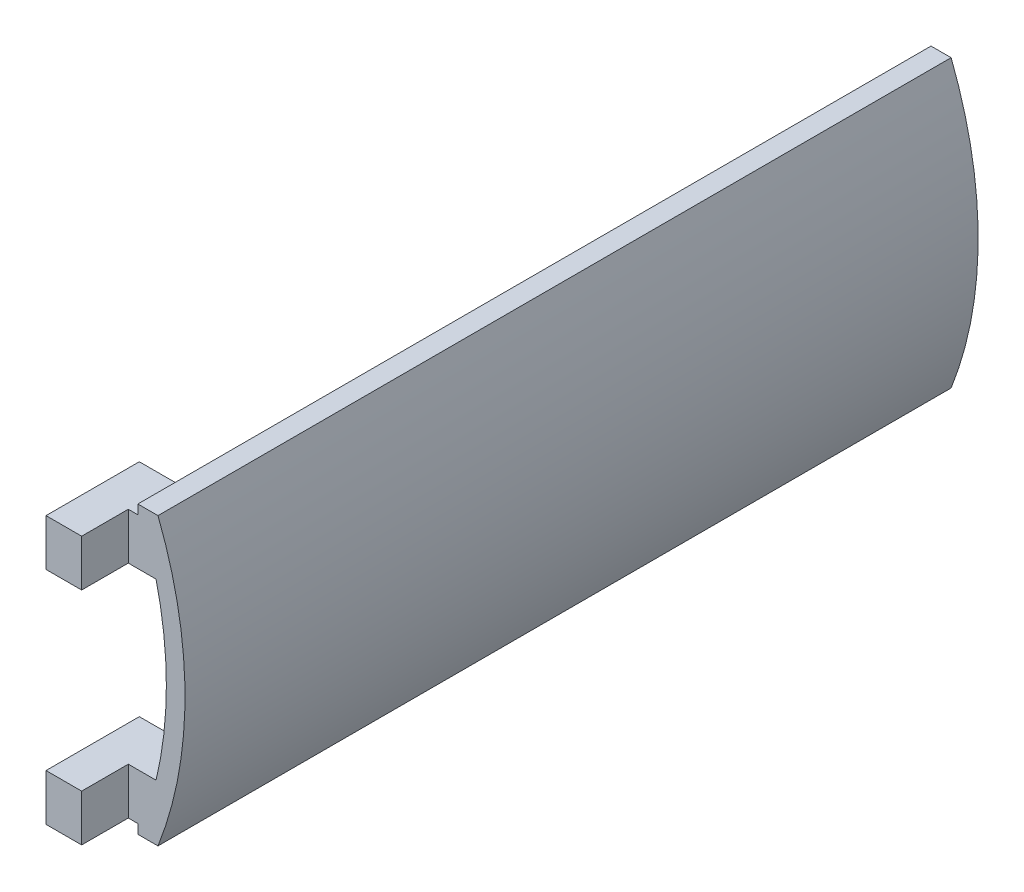
SolidWorks part; units mm, degrees
ref_plane "Спереди" through (0, 0, 0) normal (0, 0, 1) x (1, 0, 0)
ref_plane "Сверху" through (0, 0, 0) normal (0, 1, 0) x (1, 0, 0)
ref_plane "Справа" through (0, 0, 0) normal (1, 0, 0) x (0, 0, -1)
ref_plane "Плоскость4" through (0, 0, 0) normal (0, 0, -1) x (-1, 0, 0)
sketch "Эскиз1" plane through (0, 0, 0) normal (0, 0, -1) x (-1, 0, 0)
  line L0 (-36.9459, 15.3297) -> (-39.1024, 15.3297)
  line L1 (-39.1024, -15.3297) -> (-36.9459, -15.3297)
  arc A0 (-36.9459, -15.3297) -> (-36.9459, 15.3297) centre (0, 0) cw
  arc A1 (-39.1024, 15.3297) -> (-39.1024, -15.3297) centre (0, 0) ccw
extrude "Бобышка-Вытянуть1" add sketch "Эскиз1" against normal blind 85
ref_plane "Плоскость5" through (0, 0, 85) normal (0, 0, 1) x (1, 0, 0)
sketch "Эскиз2" plane through (0, 0, 85) normal (0, 0, 1) x (1, 0, 0)
  line L0 (36.9459, 15.3297) -> (36.9459, 14.3297)
  line L1 (36.9459, 14.3297) -> (32.1024, 14.3297)
  line L2 (32.1024, 14.3297) -> (32.1024, 9.3297)
  line L3 (32.1024, 9.3297) -> (38.8967, 9.3297)
  arc A0 (38.8967, 9.3297) -> (36.9459, 15.3297) centre (0, 0) ccw
extrude "Бобышка-Вытянуть2" add sketch "Эскиз2" against normal blind 5
sketch "Эскиз3" plane through (0, 0, 85) normal (0, 0, 1) x (1, 0, 0)
  line L0 (35.9229, 9.3297) -> (32.1024, 9.3297)
  line L1 (32.1024, 9.3297) -> (32.1024, 14.3297)
  line L2 (32.1024, 14.3297) -> (35.9229, 14.3297)
  line L3 (35.9229, 14.3297) -> (35.9229, 9.3297)
extrude "Бобышка-Вытянуть3" add sketch "Эскиз3" along normal blind 5
sketch "Эскиз4" plane through (0, 0, 85) normal (0, 0, 1) x (1, 0, 0)
  line L0 (32.1024, -14.3297) -> (36.9459, -14.3297)
  line L1 (36.9459, -14.3297) -> (36.9459, -15.3297)
  line L2 (38.8967, -9.3297) -> (32.1024, -9.3297)
  line L3 (32.1024, -9.3297) -> (32.1024, -14.3297)
  arc A0 (36.9459, -15.3297) -> (38.8967, -9.3297) centre (0, 0) ccw
extrude "Бобышка-Вытянуть4" add sketch "Эскиз4" against normal blind 5
sketch "Эскиз5" plane through (0, 0, 85) normal (0, 0, 1) x (1, 0, 0)
  line L0 (32.1024, -9.3297) -> (35.9229, -9.3297)
  line L1 (35.9229, -9.3297) -> (35.9229, -14.3297)
  line L2 (35.9229, -14.3297) -> (32.1024, -14.3297)
  line L3 (32.1024, -14.3297) -> (32.1024, -9.3297)
extrude "Бобышка-Вытянуть5" add sketch "Эскиз5" along normal blind 5
